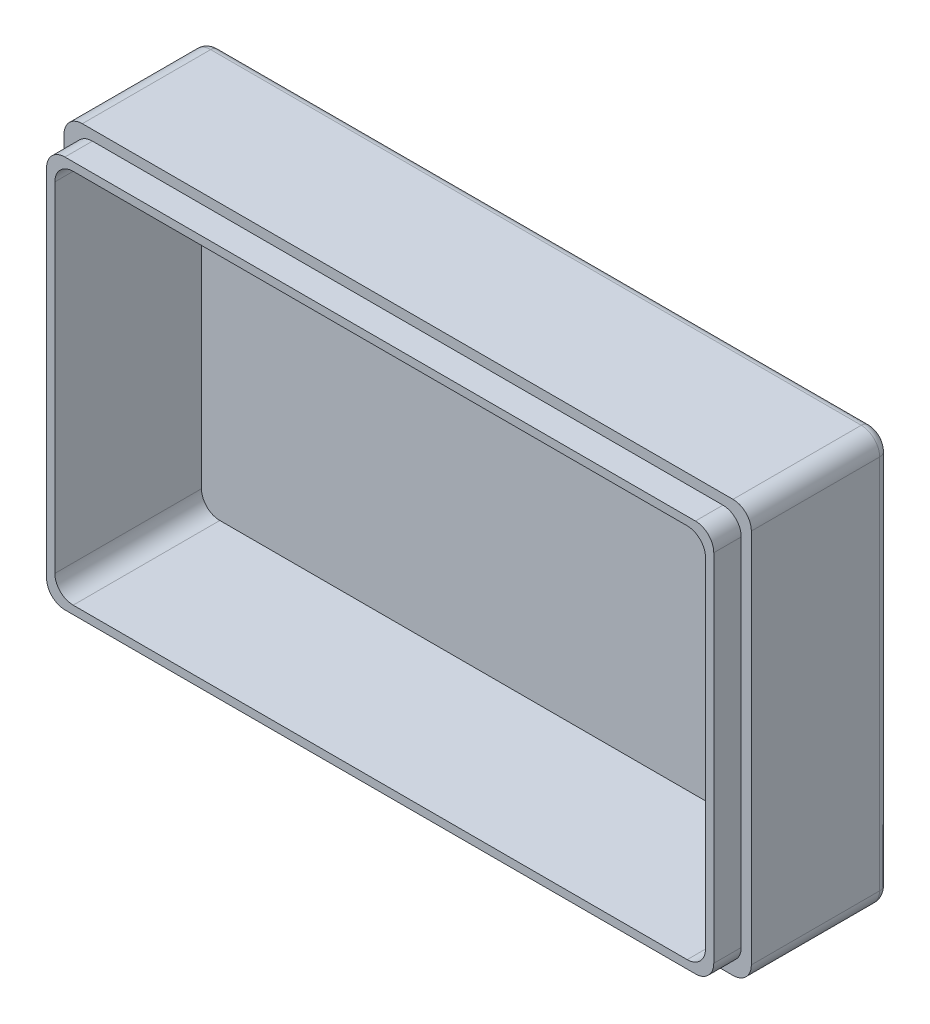
SolidWorks part; units mm, degrees
material "ABS"
ref_plane "前视基准面" through (0, 0, 0) normal (0, 0, 1) x (1, 0, 0)
ref_plane "上视基准面" through (0, 0, 0) normal (0, 1, 0) x (1, 0, 0)
ref_plane "右视基准面" through (0, 0, 0) normal (1, 0, 0) x (0, 0, -1)
sketch "草图1" plane through (0, 0, 0) normal (0, 0, 1) x (1, 0, 0)
  line L1 (-37.5, 22.5) -> (37.5, 22.5)
  line L2 (-37.5, 22.5) -> (-37.5, -22.5)
  line L3 (-37.5, -22.5) -> (37.5, -22.5)
  line L4 (37.5, 22.5) -> (37.5, -22.5)
  dimension "D1" = 75
  dimension "D2" = 45
  dimension "D3" = 37.5
  dimension "D4" = 22.5
extrude "凸台-拉伸1" add sketch "草图1" along normal blind 18
sketch "草图2" plane through (0, 0, 18) normal (0, 0, 1) x (1, 0, 0)
  line L0 (-35.5, 20.5) -> (-35.5, -20.5)
  line L1 (-35.5, -20.5) -> (35.5, -20.5)
  line L2 (35.5, -20.5) -> (35.5, 20.5)
  line L3 (35.5, 20.5) -> (-35.5, 20.5)
extrude "切除-拉伸1" cut sketch "草图2" against normal blind 16
sketch "草图3" plane through (0, 0, 18) normal (0, 0, 1) x (1, 0, 0)
  line L0 (-37.5, -22.5) -> (37.5, -22.5) construction
  line L1 (37.5, -22.5) -> (37.5, 22.5) construction
  line L2 (37.5, 22.5) -> (-37.5, 22.5) construction
  line L3 (-37.5, 22.5) -> (-37.5, -22.5) construction
  line L4 (-37.5, -22.5) -> (37.5, -22.5)
  line L5 (37.5, -22.5) -> (37.5, 22.5)
  line L6 (37.5, 22.5) -> (-37.5, 22.5)
  line L7 (-37.5, 22.5) -> (-37.5, -22.5)
  line L8 (-36.4, -21.4) -> (36.4, -21.4)
  line L9 (36.4, -21.4) -> (36.4, 21.4)
  line L10 (36.4, 21.4) -> (-36.4, 21.4)
  line L11 (-36.4, 21.4) -> (-36.4, -21.4)
  dimension "D1" = 1.1
extrude "切除-拉伸2" cut sketch "草图3" against normal blind 3
fillet "圆角1" radius 2 12 edges at (35.5, 20.5, 10) (-35.5, 20.5, 10) (-35.5, -20.5, 10) (35.5, -20.5, 10) (36.4, 21.4, 16.5) (37.5, 22.5, 7.5) (36.4, -21.4, 16.5) (37.5, -22.5, 7.5) (-36.4, -21.4, 16.5) (-37.5, -22.5, 7.5) (-36.4, 21.4, 16.5) (-37.5, 22.5, 7.5)
fillet "圆角2" radius 1 8 edges at (-36.9142, 21.9142, 0) (-37.5, 0, 0) (-36.9142, -21.9142, 0) (0, -22.5, 0) (36.9142, -21.9142, 0) (37.5, 0, 0) (36.9142, 21.9142, 0) (0, 22.5, 0)
sketch3d "URDF Reference"
  line L0 (0, 0, 0) -> (10, 0, 0) construction
  line L1 (0, 0, 0) -> (0, 0, -10) construction
  point P0 (0, 0, 0)
  point P1 (0, 0, 0)
ref_plane "基准面1" through (0, 0, 18) normal (0, 0, 1) x (1, 0, 0)
sketch "草图4" plane through (0, 0, 18) normal (0, 0, 1) x (1, 0, 0)
  line L0 (0, -21.4) -> (0, 13.3017)
  line L1 (-34.4, -21.4) -> (34.4, -21.4) construction
  line L2 (36.4, 0) -> (-29.0681, 0)
  line L3 (36.4, -19.4) -> (36.4, 19.4) construction
  point P9 (0, 0)
